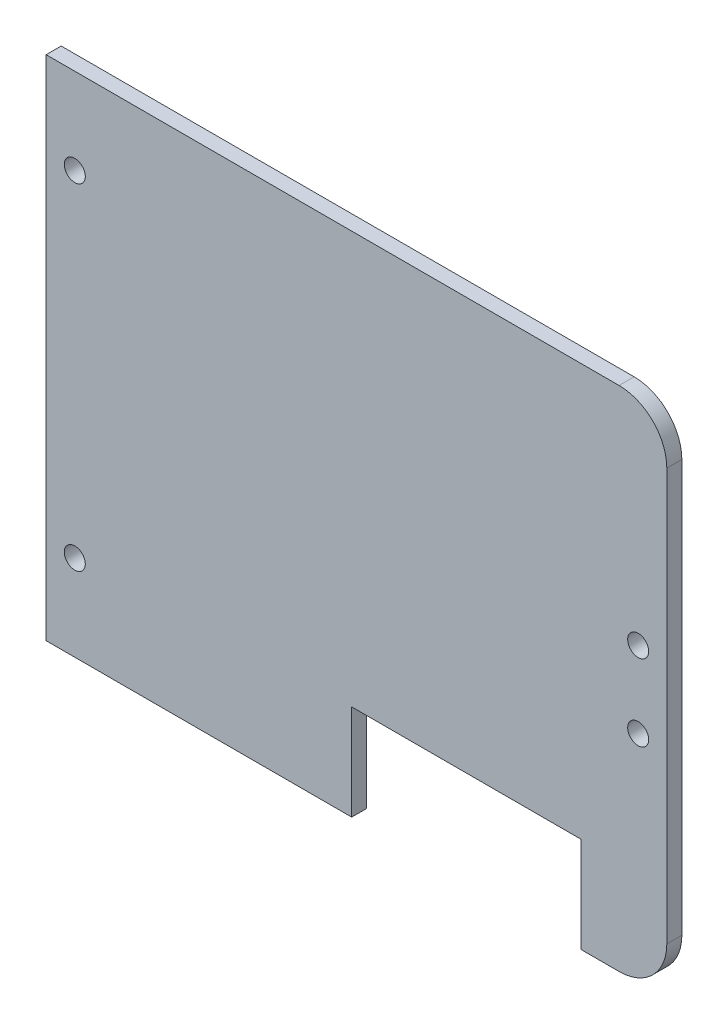
SolidWorks part; units mm, degrees
ref_plane "Front Plane" through (0, 0, 0) normal (0, 0, 1) x (1, 0, 0)
ref_plane "Top Plane" through (0, 0, 0) normal (0, 1, 0) x (1, 0, 0)
ref_plane "Right Plane" through (0, 0, 0) normal (1, 0, 0) x (0, 0, -1)
sketch "BPR2 PCB Outline" plane through (0, 0, 0) normal (0, 0, 1) x (1, 0, 0)
  line L0 (0, 0) -> (0, 53.15)
  line L1 (0, 53.15) -> (60, 53.15)
  line L2 (65, 48.15) -> (65, 5)
  line L3 (60, 0) -> (56, 0)
  line L4 (56, 0) -> (56, 10)
  line L5 (56, 10) -> (32, 10)
  line L6 (32, 10) -> (32, 0)
  line L7 (32, 0) -> (0, 0)
  arc A0 (65, 48.15) -> (60, 53.15) centre (60, 48.15) ccw
  arc A1 (60, 0) -> (65, 5) centre (60, 5) ccw
  circle A2 centre (3, 9) radius 1.1
  circle A3 centre (62, 22.575) radius 1.1
  circle A4 centre (3, 44.15) radius 1.1
  circle A5 centre (62, 30.575) radius 1.1
sketch "23" plane through (0, 0, 0) normal (0, 0, 1) x (1, 0, 0)
  point P0 (0, 0)
sketch "48" plane through (0, 0, 0) normal (0, 0, 1) x (1, 0, 0)
  line L0 (2, 15) -> (3.0323, 15)
  line L1 (4.0323, 15) -> (5.0645, 15)
  line L2 (6.0645, 15) -> (7.0968, 15)
  line L3 (8.0968, 15) -> (9.129, 15)
  line L4 (10.129, 15) -> (11.1613, 15)
  line L5 (12.1613, 15) -> (13.1935, 15)
  line L6 (14.1935, 15) -> (15.2258, 15)
  line L7 (16.2258, 15) -> (17.2581, 15)
  line L8 (18.2581, 15) -> (19.2903, 15)
  line L9 (20.2903, 15) -> (21.3226, 15)
  line L10 (22.3226, 15) -> (23.3548, 15)
  line L11 (24.3548, 15) -> (25.3871, 15)
  line L12 (26.3871, 15) -> (27.4194, 15)
  line L13 (28.4194, 15) -> (29.4516, 15)
  line L14 (30.4516, 15) -> (31.4839, 15)
  line L15 (32.4839, 15) -> (33.5161, 15)
  line L16 (34.5161, 15) -> (35.5484, 15)
  line L17 (36.5484, 15) -> (37.5806, 15)
  line L18 (38.5806, 15) -> (39.6129, 15)
  line L19 (40.6129, 15) -> (41.6452, 15)
  line L20 (42.6452, 15) -> (43.6774, 15)
  line L21 (44.6774, 15) -> (45.7097, 15)
  line L22 (46.7097, 15) -> (47.7419, 15)
  line L23 (48.7419, 15) -> (49.7742, 15)
  line L24 (50.7742, 15) -> (51.8065, 15)
  line L25 (52.8065, 15) -> (53.8387, 15)
  line L26 (54.8387, 15) -> (55.871, 15)
  line L27 (56.871, 15) -> (57.9032, 15)
  line L28 (58.9032, 15) -> (59.9355, 15)
  line L29 (60.9355, 15) -> (61.9677, 15)
  line L30 (62.9677, 15) -> (64, 15)
  line L31 (2, 16.575) -> (3.0323, 16.575)
  line L32 (4.0323, 16.575) -> (5.0645, 16.575)
  line L33 (6.0645, 16.575) -> (7.0968, 16.575)
  line L34 (8.0968, 16.575) -> (9.129, 16.575)
  line L35 (10.129, 16.575) -> (11.1613, 16.575)
  line L36 (12.1613, 16.575) -> (13.1935, 16.575)
  line L37 (14.1935, 16.575) -> (15.2258, 16.575)
  line L38 (16.2258, 16.575) -> (17.2581, 16.575)
  line L39 (18.2581, 16.575) -> (19.2903, 16.575)
  line L40 (20.2903, 16.575) -> (21.3226, 16.575)
  line L41 (22.3226, 16.575) -> (23.3548, 16.575)
  line L42 (24.3548, 16.575) -> (25.3871, 16.575)
  line L43 (26.3871, 16.575) -> (27.4194, 16.575)
  line L44 (28.4194, 16.575) -> (29.4516, 16.575)
  line L45 (30.4516, 16.575) -> (31.4839, 16.575)
  line L46 (32.4839, 16.575) -> (33.5161, 16.575)
  line L47 (34.5161, 16.575) -> (35.5484, 16.575)
  line L48 (36.5484, 16.575) -> (37.5806, 16.575)
  line L49 (38.5806, 16.575) -> (39.6129, 16.575)
  line L50 (40.6129, 16.575) -> (41.6452, 16.575)
  line L51 (42.6452, 16.575) -> (43.6774, 16.575)
  line L52 (44.6774, 16.575) -> (45.7097, 16.575)
  line L53 (46.7097, 16.575) -> (47.7419, 16.575)
  line L54 (48.7419, 16.575) -> (49.7742, 16.575)
  line L55 (50.7742, 16.575) -> (51.8065, 16.575)
  line L56 (52.8065, 16.575) -> (53.8387, 16.575)
  line L57 (54.8387, 16.575) -> (55.871, 16.575)
  line L58 (56.871, 16.575) -> (57.9032, 16.575)
  line L59 (58.9032, 16.575) -> (59.9355, 16.575)
  line L60 (60.9355, 16.575) -> (61.9677, 16.575)
  line L61 (62.9677, 16.575) -> (64, 16.575)
  line L62 (2, 36.575) -> (3.0323, 36.575)
  line L63 (4.0323, 36.575) -> (5.0645, 36.575)
  line L64 (6.0645, 36.575) -> (7.0968, 36.575)
  line L65 (8.0968, 36.575) -> (9.129, 36.575)
  line L66 (10.129, 36.575) -> (11.1613, 36.575)
  line L67 (12.1613, 36.575) -> (13.1935, 36.575)
  line L68 (14.1935, 36.575) -> (15.2258, 36.575)
  line L69 (16.2258, 36.575) -> (17.2581, 36.575)
  line L70 (18.2581, 36.575) -> (19.2903, 36.575)
  line L71 (20.2903, 36.575) -> (21.3226, 36.575)
  line L72 (22.3226, 36.575) -> (23.3548, 36.575)
  line L73 (24.3548, 36.575) -> (25.3871, 36.575)
  line L74 (26.3871, 36.575) -> (27.4194, 36.575)
  line L75 (28.4194, 36.575) -> (29.4516, 36.575)
  line L76 (30.4516, 36.575) -> (31.4839, 36.575)
  line L77 (32.4839, 36.575) -> (33.5161, 36.575)
  line L78 (34.5161, 36.575) -> (35.5484, 36.575)
  line L79 (36.5484, 36.575) -> (37.5806, 36.575)
  line L80 (38.5806, 36.575) -> (39.6129, 36.575)
  line L81 (40.6129, 36.575) -> (41.6452, 36.575)
  line L82 (42.6452, 36.575) -> (43.6774, 36.575)
  line L83 (44.6774, 36.575) -> (45.7097, 36.575)
  line L84 (46.7097, 36.575) -> (47.7419, 36.575)
  line L85 (48.7419, 36.575) -> (49.7742, 36.575)
  line L86 (50.7742, 36.575) -> (51.8065, 36.575)
  line L87 (52.8065, 36.575) -> (53.8387, 36.575)
  line L88 (54.8387, 36.575) -> (55.871, 36.575)
  line L89 (56.871, 36.575) -> (57.9032, 36.575)
  line L90 (58.9032, 36.575) -> (59.9355, 36.575)
  line L91 (60.9355, 36.575) -> (61.9677, 36.575)
  line L92 (62.9677, 36.575) -> (64, 36.575)
  line L93 (2, 38.15) -> (3.0385, 38.15)
  line L94 (4.0385, 38.15) -> (5.0769, 38.15)
  line L95 (6.0769, 38.15) -> (7.1154, 38.15)
  line L96 (8.1154, 38.15) -> (9.1538, 38.15)
  line L97 (10.1538, 38.15) -> (11.1923, 38.15)
  line L98 (12.1923, 38.15) -> (13.2308, 38.15)
  line L99 (14.2308, 38.15) -> (15.2692, 38.15)
  line L100 (16.2692, 38.15) -> (17.3077, 38.15)
  line L101 (18.3077, 38.15) -> (19.3462, 38.15)
  line L102 (20.3462, 38.15) -> (21.3846, 38.15)
  line L103 (22.3846, 38.15) -> (23.4231, 38.15)
  line L104 (24.4231, 38.15) -> (25.4615, 38.15)
  line L105 (26.4615, 38.15) -> (27.5, 38.15)
  line L106 (27.5, 38.15) -> (28.525, 38.15)
  line L107 (29.525, 38.15) -> (30.55, 38.15)
  line L108 (31.55, 38.15) -> (32.575, 38.15)
  line L109 (33.575, 38.15) -> (34.6, 38.15)
  line L110 (35.6, 38.15) -> (36.625, 38.15)
  line L111 (37.625, 38.15) -> (38.65, 38.15)
  line L112 (39.65, 38.15) -> (40.675, 38.15)
  line L113 (41.675, 38.15) -> (42.7, 38.15)
  line L114 (43.7, 38.15) -> (44.725, 38.15)
  line L115 (45.725, 38.15) -> (46.75, 38.15)
  line L116 (47.75, 38.15) -> (48.775, 38.15)
  line L117 (49.775, 38.15) -> (50.8, 38.15)
  line L118 (50.8, 38.15) -> (51.8286, 38.15)
  line L119 (52.8286, 38.15) -> (53.8571, 38.15)
  line L120 (54.8571, 38.15) -> (55.8857, 38.15)
  line L121 (56.8857, 38.15) -> (57.9143, 38.15)
  line L122 (58.9143, 38.15) -> (59.9429, 38.15)
  line L123 (60.9429, 38.15) -> (61.9714, 38.15)
  line L124 (62.9714, 38.15) -> (64, 38.15)
  line L125 (27.5, 38.15) -> (27.5, 41.14)
  line L126 (27.5, 41.8214) -> (27.5, 41.9586)
  line L127 (27.5, 42.64) -> (27.5, 45.63)
  line L128 (27.5, 46.3114) -> (27.5, 46.4487)
  line L129 (27.5, 47.13) -> (27.5, 50.12)
  line L130 (27.5, 50.8013) -> (27.5, 50.9387)
  line L131 (27.5, 51.62) -> (27.5, 54.61)
  line L132 (27.5, 54.61) -> (30.1333, 54.61)
  line L133 (30.8147, 54.61) -> (30.952, 54.61)
  line L134 (31.6333, 54.61) -> (34.2667, 54.61)
  line L135 (34.948, 54.61) -> (35.0853, 54.61)
  line L136 (35.7667, 54.61) -> (38.4, 54.61)
  line L137 (39.0814, 54.61) -> (39.2187, 54.61)
  line L138 (39.9, 54.61) -> (42.5333, 54.61)
  line L139 (43.2147, 54.61) -> (43.352, 54.61)
  line L140 (44.0333, 54.61) -> (46.6667, 54.61)
  line L141 (47.348, 54.61) -> (47.4853, 54.61)
  line L142 (48.1667, 54.61) -> (50.8, 54.61)
  line L143 (50.8, 54.61) -> (50.82, 54.61)
  line L144 (27.5, -1.46) -> (30.1333, -1.46)
  line L145 (30.8147, -1.46) -> (30.952, -1.46)
  line L146 (31.6333, -1.46) -> (34.2667, -1.46)
  line L147 (34.948, -1.46) -> (35.0853, -1.46)
  line L148 (35.7667, -1.46) -> (38.4, -1.46)
  line L149 (39.0814, -1.46) -> (39.2187, -1.46)
  line L150 (39.9, -1.46) -> (42.5333, -1.46)
  line L151 (43.2147, -1.46) -> (43.352, -1.46)
  line L152 (44.0333, -1.46) -> (46.6667, -1.46)
  line L153 (47.348, -1.46) -> (47.4853, -1.46)
  line L154 (48.1667, -1.46) -> (50.8, -1.46)
  line L155 (50.8, -1.46) -> (50.82, -1.46)
  line L156 (27.5, 14.82) -> (27.5, 11.875)
  line L157 (27.5, 11.1936) -> (27.5, 11.0564)
  line L158 (27.5, 10.375) -> (27.5, 7.43)
  line L159 (27.5, 6.7487) -> (27.5, 6.6114)
  line L160 (27.5, 5.93) -> (27.5, 2.985)
  line L161 (27.5, 2.3037) -> (27.5, 2.1663)
  line L162 (27.5, 1.485) -> (27.5, -1.46)
  line L163 (50.8, 38.15) -> (50.8, 41.14)
  line L164 (50.8, 41.8214) -> (50.8, 41.9586)
  line L165 (50.8, 42.64) -> (50.8, 45.63)
  line L166 (50.8, 46.3114) -> (50.8, 46.4487)
  line L167 (50.8, 47.13) -> (50.8, 50.12)
  line L168 (50.8, 50.8013) -> (50.8, 50.9387)
  line L169 (50.8, 51.62) -> (50.8, 54.61)
  line L170 (50.8, 14.82) -> (50.8, 11.875)
  line L171 (50.8, 11.1936) -> (50.8, 11.0564)
  line L172 (50.8, 10.375) -> (50.8, 7.43)
  line L173 (50.8, 6.7487) -> (50.8, 6.6114)
  line L174 (50.8, 5.93) -> (50.8, 2.985)
  line L175 (50.8, 2.3037) -> (50.8, 2.1663)
  line L176 (50.8, 1.485) -> (50.8, -1.46)
  arc A0 (27.5317, 41.14) -> (27.4683, 41.14) centre (27.5, 41.14) ccw
  arc A1 (27.4683, 38.15) -> (27.5317, 38.15) centre (27.5, 38.15) ccw
  arc A2 (27.5317, 41.9586) -> (27.4683, 41.9586) centre (27.5, 41.9586) ccw
  arc A3 (27.4683, 41.8214) -> (27.5317, 41.8214) centre (27.5, 41.8214) ccw
  arc A4 (27.5317, 45.63) -> (27.4683, 45.63) centre (27.5, 45.63) ccw
  arc A5 (27.4683, 42.64) -> (27.5317, 42.64) centre (27.5, 42.64) ccw
  arc A6 (27.5317, 46.4487) -> (27.4683, 46.4487) centre (27.5, 46.4487) ccw
  arc A7 (27.4683, 46.3114) -> (27.5317, 46.3114) centre (27.5, 46.3114) ccw
  arc A8 (27.5317, 50.12) -> (27.4683, 50.12) centre (27.5, 50.12) ccw
  arc A9 (27.4683, 47.13) -> (27.5317, 47.13) centre (27.5, 47.13) ccw
  arc A10 (27.5317, 50.9387) -> (27.4683, 50.9387) centre (27.5, 50.9387) ccw
  arc A11 (27.4683, 50.8013) -> (27.5317, 50.8013) centre (27.5, 50.8013) ccw
  arc A12 (27.5317, 54.61) -> (27.4683, 54.61) centre (27.5, 54.61) ccw
  arc A13 (27.4683, 51.62) -> (27.5317, 51.62) centre (27.5, 51.62) ccw
  arc A14 (30.1333, 54.5782) -> (30.1333, 54.6418) centre (30.1333, 54.61) ccw
  arc A15 (27.5, 54.6418) -> (27.5, 54.5782) centre (27.5, 54.61) ccw
  arc A16 (30.952, 54.5782) -> (30.952, 54.6418) centre (30.952, 54.61) ccw
  arc A17 (30.8147, 54.6418) -> (30.8147, 54.5782) centre (30.8147, 54.61) ccw
  arc A18 (34.2667, 54.5782) -> (34.2667, 54.6418) centre (34.2667, 54.61) ccw
  arc A19 (31.6333, 54.6418) -> (31.6333, 54.5782) centre (31.6333, 54.61) ccw
  arc A20 (35.0853, 54.5782) -> (35.0853, 54.6418) centre (35.0853, 54.61) ccw
  arc A21 (34.948, 54.6418) -> (34.948, 54.5782) centre (34.948, 54.61) ccw
  arc A22 (38.4, 54.5782) -> (38.4, 54.6418) centre (38.4, 54.61) ccw
  arc A23 (35.7667, 54.6418) -> (35.7667, 54.5782) centre (35.7667, 54.61) ccw
  arc A24 (39.2187, 54.5782) -> (39.2187, 54.6418) centre (39.2187, 54.61) ccw
  arc A25 (39.0814, 54.6418) -> (39.0814, 54.5782) centre (39.0814, 54.61) ccw
  arc A26 (42.5333, 54.5782) -> (42.5333, 54.6418) centre (42.5333, 54.61) ccw
  arc A27 (39.9, 54.6418) -> (39.9, 54.5782) centre (39.9, 54.61) ccw
  arc A28 (43.352, 54.5782) -> (43.352, 54.6418) centre (43.352, 54.61) ccw
  arc A29 (43.2147, 54.6418) -> (43.2147, 54.5782) centre (43.2147, 54.61) ccw
  arc A30 (46.6667, 54.5782) -> (46.6667, 54.6418) centre (46.6667, 54.61) ccw
  arc A31 (44.0333, 54.6418) -> (44.0333, 54.5782) centre (44.0333, 54.61) ccw
  arc A32 (47.4853, 54.5782) -> (47.4853, 54.6418) centre (47.4853, 54.61) ccw
  arc A33 (47.348, 54.6418) -> (47.348, 54.5782) centre (47.348, 54.61) ccw
  arc A34 (50.8, 54.5782) -> (50.8, 54.6418) centre (50.8, 54.61) ccw
  arc A35 (48.1667, 54.6418) -> (48.1667, 54.5782) centre (48.1667, 54.61) ccw
  arc A36 (50.82, 54.5782) -> (50.82, 54.6418) centre (50.82, 54.61) ccw
  arc A37 (50.8, 54.6418) -> (50.8, 54.5782) centre (50.8, 54.61) ccw
  arc A38 (30.1333, -1.4917) -> (30.1333, -1.4283) centre (30.1333, -1.46) ccw
  arc A39 (27.5, -1.4283) -> (27.5, -1.4917) centre (27.5, -1.46) ccw
  arc A40 (30.952, -1.4917) -> (30.952, -1.4283) centre (30.952, -1.46) ccw
  arc A41 (30.8147, -1.4283) -> (30.8147, -1.4917) centre (30.8147, -1.46) ccw
  arc A42 (34.2667, -1.4917) -> (34.2667, -1.4283) centre (34.2667, -1.46) ccw
  arc A43 (31.6333, -1.4283) -> (31.6333, -1.4917) centre (31.6333, -1.46) ccw
  arc A44 (35.0853, -1.4917) -> (35.0853, -1.4283) centre (35.0853, -1.46) ccw
  arc A45 (34.948, -1.4283) -> (34.948, -1.4917) centre (34.948, -1.46) ccw
  arc A46 (38.4, -1.4917) -> (38.4, -1.4283) centre (38.4, -1.46) ccw
  arc A47 (35.7667, -1.4283) -> (35.7667, -1.4917) centre (35.7667, -1.46) ccw
  arc A48 (39.2187, -1.4917) -> (39.2187, -1.4283) centre (39.2187, -1.46) ccw
  arc A49 (39.0814, -1.4283) -> (39.0814, -1.4917) centre (39.0814, -1.46) ccw
  arc A50 (42.5333, -1.4917) -> (42.5333, -1.4283) centre (42.5333, -1.46) ccw
  arc A51 (39.9, -1.4283) -> (39.9, -1.4917) centre (39.9, -1.46) ccw
  arc A52 (43.352, -1.4917) -> (43.352, -1.4283) centre (43.352, -1.46) ccw
  arc A53 (43.2147, -1.4283) -> (43.2147, -1.4917) centre (43.2147, -1.46) ccw
  arc A54 (46.6667, -1.4917) -> (46.6667, -1.4283) centre (46.6667, -1.46) ccw
  arc A55 (44.0333, -1.4283) -> (44.0333, -1.4917) centre (44.0333, -1.46) ccw
  arc A56 (47.4853, -1.4917) -> (47.4853, -1.4283) centre (47.4853, -1.46) ccw
  arc A57 (47.348, -1.4283) -> (47.348, -1.4917) centre (47.348, -1.46) ccw
  arc A58 (50.8, -1.4917) -> (50.8, -1.4283) centre (50.8, -1.46) ccw
  arc A59 (48.1667, -1.4283) -> (48.1667, -1.4917) centre (48.1667, -1.46) ccw
  arc A60 (50.82, -1.4917) -> (50.82, -1.4283) centre (50.82, -1.46) ccw
  arc A61 (50.8, -1.4283) -> (50.8, -1.4917) centre (50.8, -1.46) ccw
  arc A62 (27.4683, 11.875) -> (27.5317, 11.875) centre (27.5, 11.875) ccw
  arc A63 (27.5317, 14.82) -> (27.4683, 14.82) centre (27.5, 14.82) ccw
  arc A64 (27.4683, 11.0564) -> (27.5317, 11.0564) centre (27.5, 11.0564) ccw
  arc A65 (27.5317, 11.1936) -> (27.4683, 11.1936) centre (27.5, 11.1936) ccw
  arc A66 (27.4683, 7.43) -> (27.5317, 7.43) centre (27.5, 7.43) ccw
  arc A67 (27.5317, 10.375) -> (27.4683, 10.375) centre (27.5, 10.375) ccw
  arc A68 (27.4683, 6.6114) -> (27.5317, 6.6114) centre (27.5, 6.6114) ccw
  arc A69 (27.5317, 6.7487) -> (27.4683, 6.7487) centre (27.5, 6.7487) ccw
  arc A70 (27.4683, 2.985) -> (27.5317, 2.985) centre (27.5, 2.985) ccw
  arc A71 (27.5317, 5.93) -> (27.4683, 5.93) centre (27.5, 5.93) ccw
  arc A72 (27.4683, 2.1663) -> (27.5317, 2.1663) centre (27.5, 2.1663) ccw
  arc A73 (27.5317, 2.3037) -> (27.4683, 2.3037) centre (27.5, 2.3037) ccw
  arc A74 (27.4683, -1.46) -> (27.5317, -1.46) centre (27.5, -1.46) ccw
  arc A75 (27.5317, 1.485) -> (27.4683, 1.485) centre (27.5, 1.485) ccw
  arc A76 (50.8318, 41.14) -> (50.7683, 41.14) centre (50.8, 41.14) ccw
  arc A77 (50.7683, 38.15) -> (50.8318, 38.15) centre (50.8, 38.15) ccw
  arc A78 (50.8318, 41.9586) -> (50.7683, 41.9586) centre (50.8, 41.9586) ccw
  arc A79 (50.7683, 41.8214) -> (50.8318, 41.8214) centre (50.8, 41.8214) ccw
  arc A80 (50.8318, 45.63) -> (50.7683, 45.63) centre (50.8, 45.63) ccw
  arc A81 (50.7683, 42.64) -> (50.8318, 42.64) centre (50.8, 42.64) ccw
  arc A82 (50.8318, 46.4487) -> (50.7683, 46.4487) centre (50.8, 46.4487) ccw
  arc A83 (50.7683, 46.3114) -> (50.8318, 46.3114) centre (50.8, 46.3114) ccw
  arc A84 (50.8318, 50.12) -> (50.7683, 50.12) centre (50.8, 50.12) ccw
  arc A85 (50.7683, 47.13) -> (50.8318, 47.13) centre (50.8, 47.13) ccw
  arc A86 (50.8318, 50.9387) -> (50.7683, 50.9387) centre (50.8, 50.9387) ccw
  arc A87 (50.7683, 50.8013) -> (50.8318, 50.8013) centre (50.8, 50.8013) ccw
  arc A88 (50.8318, 54.61) -> (50.7683, 54.61) centre (50.8, 54.61) ccw
  arc A89 (50.7683, 51.62) -> (50.8318, 51.62) centre (50.8, 51.62) ccw
  arc A90 (50.7683, 11.875) -> (50.8318, 11.875) centre (50.8, 11.875) ccw
  arc A91 (50.8318, 14.82) -> (50.7683, 14.82) centre (50.8, 14.82) ccw
  arc A92 (50.7683, 11.0564) -> (50.8318, 11.0564) centre (50.8, 11.0564) ccw
  arc A93 (50.8318, 11.1936) -> (50.7683, 11.1936) centre (50.8, 11.1936) ccw
  arc A94 (50.7683, 7.43) -> (50.8318, 7.43) centre (50.8, 7.43) ccw
  arc A95 (50.8318, 10.375) -> (50.7683, 10.375) centre (50.8, 10.375) ccw
  arc A96 (50.7683, 6.6114) -> (50.8318, 6.6114) centre (50.8, 6.6114) ccw
  arc A97 (50.8318, 6.7487) -> (50.7683, 6.7487) centre (50.8, 6.7487) ccw
  arc A98 (50.7683, 2.985) -> (50.8318, 2.985) centre (50.8, 2.985) ccw
  arc A99 (50.8318, 5.93) -> (50.7683, 5.93) centre (50.8, 5.93) ccw
  arc A100 (50.7683, 2.1663) -> (50.8318, 2.1663) centre (50.8, 2.1663) ccw
  arc A101 (50.8318, 2.3037) -> (50.7683, 2.3037) centre (50.8, 2.3037) ccw
  arc A102 (50.7683, -1.46) -> (50.8318, -1.46) centre (50.8, -1.46) ccw
  arc A103 (50.8318, 1.485) -> (50.7683, 1.485) centre (50.8, 1.485) ccw
extrude "Boss-Extrude1" add sketch "BPR2 PCB Outline" against normal blind 1.5748
sketch "Label BPR Inside" plane through (0, 0, 0) normal (0, 0, 1) x (1, 0, 0)
  line L0 (0, 53.15) -> (0, 0) construction
  line L1 (60, 53.15) -> (0, 53.15) construction
  text T0 "BPR INSIDE" font "Courier New" height 0.25
  dimension "D1" = 0.5
  dimension "D2" = 1
sketch "Label BPR Outside" plane through (0, 0, -1.5748) normal (0, 0, 1) x (1, 0, 0)
  line L1 (0, 53.15) -> (0, 0) construction
  line L2 (60, 53.15) -> (0, 53.15) construction
  text T0 "BPR OUTSIDE" font "Courier New" height 0.25
  dimension "D1" = 3
  dimension "D2" = 1
